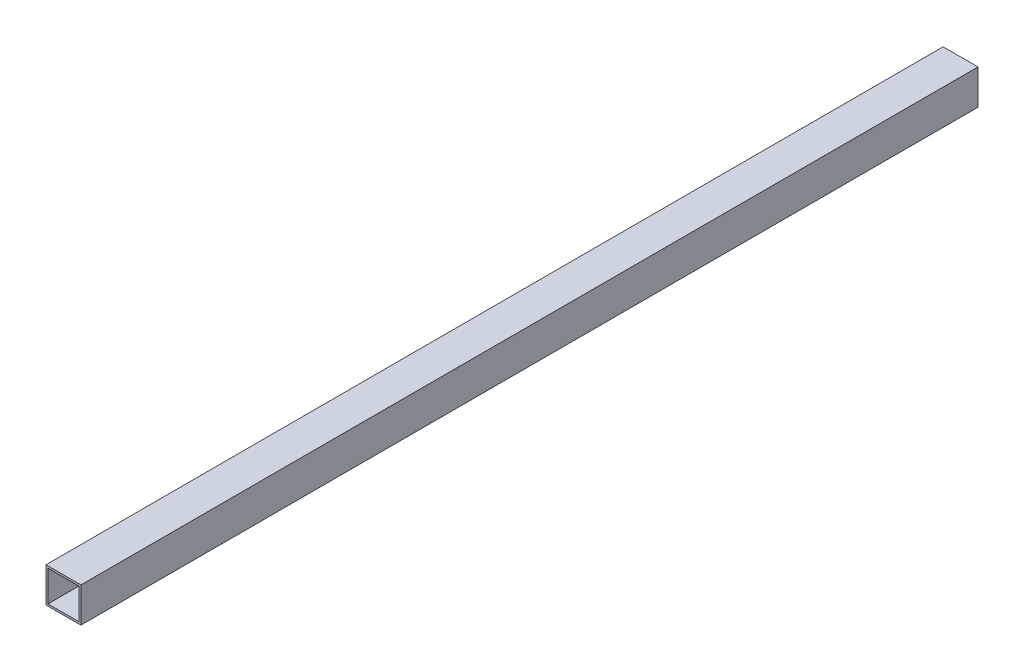
SolidWorks part; units mm, degrees
material "7075-T6 (SN)"
ref_plane "Front Plane" through (0, 0, 0) normal (0, 0, 1) x (1, 0, 0)
ref_plane "Top Plane" through (0, 0, 0) normal (0, 1, 0) x (1, 0, 0)
ref_plane "Right Plane" through (0, 0, 0) normal (1, 0, 0) x (0, 0, -1)
sketch "Sketch1" plane through (0, 0, 0) normal (0, 0, 1) x (1, 0, 0)
  line L1 (-15.5, 15.5) -> (15.5, 15.5)
  line L2 (-15.5, 15.5) -> (-15.5, -15.5)
  line L3 (-15.5, -15.5) -> (15.5, -15.5)
  line L4 (15.5, 15.5) -> (15.5, -15.5)
  line L5 (-15.5, 15.5) -> (15.5, -15.5) construction
  line L6 (-15.5, -15.5) -> (15.5, 15.5) construction
  line L7 (-17.5, 17.5) -> (17.5, 17.5)
  line L8 (-17.5, 17.5) -> (-17.5, -17.5)
  line L9 (-17.5, -17.5) -> (17.5, -17.5)
  line L10 (17.5, 17.5) -> (17.5, -17.5)
  line L11 (-17.5, 17.5) -> (17.5, -17.5) construction
  line L12 (-17.5, -17.5) -> (17.5, 17.5) construction
  point P1 (0, 0)
  point P6 (0, 0)
  dimension "D1" = 31
  dimension "D2" = 31
  dimension "D3" = 35
  dimension "D4" = 35
extrude "Boss-Extrude1" add sketch "Sketch1" along normal blind 900
